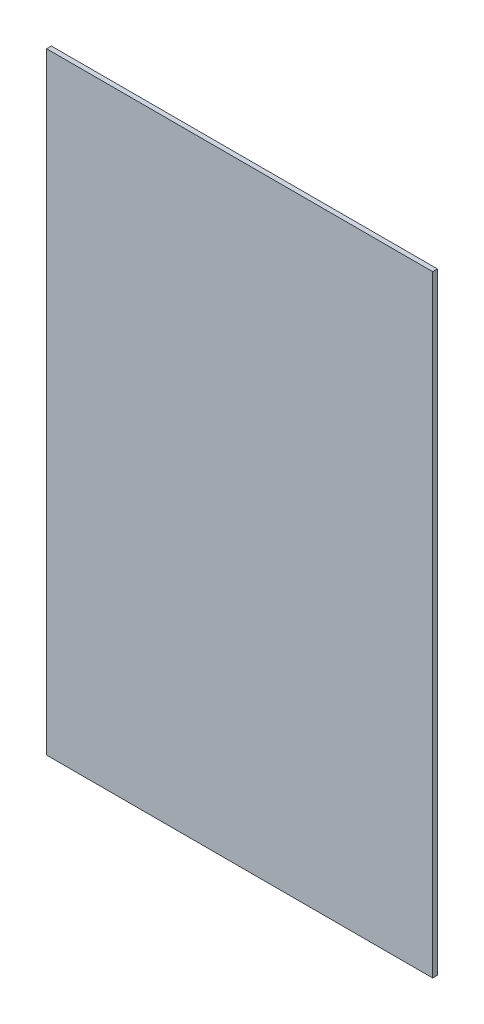
SolidWorks part; units mm, degrees
ref_plane "Front Plane" through (0, 0, 0) normal (0, 0, 1) x (1, 0, 0)
ref_plane "Top Plane" through (0, 0, 0) normal (0, 1, 0) x (1, 0, 0)
ref_plane "Right Plane" through (0, 0, 0) normal (1, 0, 0) x (0, 0, -1)
sketch "Sketch1" plane through (0, 0, 0) normal (0, 0, 1) x (1, 0, 0)
  line L1 (-53.2088, 16.5) -> (11.7912, 16.5)
  line L2 (-53.2088, 16.5) -> (-53.2088, -86.5)
  line L3 (-53.2088, -86.5) -> (11.7912, -86.5)
  line L4 (11.7912, 16.5) -> (11.7912, -86.5)
  dimension "D1" = 103
  dimension "D2" = 65
extrude "Boss-Extrude1" add sketch "Sketch1" along normal blind 0.8
